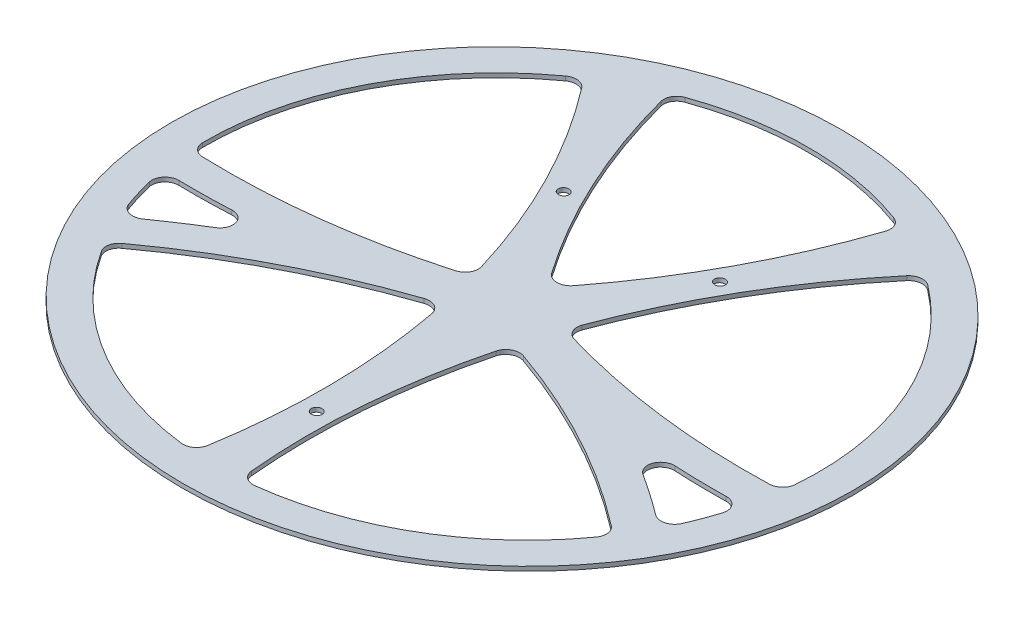
SolidWorks part; units mm, degrees
ref_plane "Front Plane" through (0, 0, 0) normal (0, 0, 1) x (1, 0, 0)
ref_plane "Top Plane" through (0, 0, 0) normal (0, 1, 0) x (1, 0, 0)
ref_plane "Right Plane" through (0, 0, 0) normal (1, 0, 0) x (0, 0, -1)
sketch3d "3DSketch1"
  line L1 (0, 87.7693, 116.125) -> (0, 80.6293, 116.125) construction
  line L2 (0, 80.6293, 116.125) -> (0, 84.5443, 116.125) construction
  line L3 (-59, 71.1385, -129.5485) -> (-59, 79.2077, -128.8425) construction
  circle A4 centre (-59, 71.1385, -129.5485) radius 2.925 construction
  circle A5 centre (-59, 79.2077, -128.8425) radius 1.425 construction
  point P20 (-59, 74.0524, -129.2935)
  point P23 (-59, 80.6273, -128.7183)
sketch "Sketch1" plane through (0, 79.1663, -2.7669) normal (0, -0.9994, 0.0349) x (0, -0.0349, -0.9994)
  line L0 (282.5006, 0) -> (-225.4994, 0) construction
  line L1 (335.28, 0) -> (-335.28, 0) construction
  line L2 (126.9846, -59) -> (125.9973, -59) construction
  line L3 (12.788, 0) -> (-12.788, 0) construction
  line L4 (126.5432, 59) -> (-119.1198, 540.9432) construction
  line L5 (126.5432, 59) -> (10.7966, 0) construction
  line L6 (-119.1198, 0) -> (125.9973, 0) construction
  circle A0 centre (28.5006, 0) radius 248.894
  circle A2 centre (-119.1198, 0) radius 4
  circle A3 centre (126.5432, -59) radius 4
  circle A4 centre (126.5432, 59) radius 4
  arc A5 (238.0819, -78.767) -> (238.0819, 78.767) centre (28.5006, 0) ccw
  circle A6 centre (126.5432, 59) radius 12.5
  circle A7 centre (126.5432, -59) radius 12.5
  circle A8 centre (-119.1198, 0) radius 12.5
  arc A9 (-184.9866, 16.621) -> (-7.7838, 24.3616) centre (-119.1198, 540.9432) ccw
  arc A10 (-184.9866, -16.621) -> (-7.7838, -24.3616) centre (-119.1198, -540.9432) cw
  arc A11 (225.9535, 84.8583) -> (66.5854, 8.1579) centre (372.2061, -422.9432) ccw
  arc A12 (225.9535, -84.8583) -> (66.5854, -8.1579) centre (372.2061, 422.9432) cw
  circle A13 centre (28.5006, 0) radius 223.894 construction
  arc A14 (205.7547, 136.7828) -> (18.3529, 223.664) centre (28.5006, 0) ccw
  arc A15 (-193.6629, -27.7839) -> (-94.7562, -186.9126) centre (28.5006, 0) ccw
  arc A16 (43.3324, 38.0899) -> (203.9515, 122.76) centre (-119.1198, 540.9432) ccw
  arc A17 (8.8118, -214.0115) -> (30.6777, -44.7397) centre (536.9543, -196.1868) cw
  arc A18 (-81.3637, -184.7117) -> (-0.4726, -37.4988) centre (-498.1628, 140.1432) ccw
  arc A19 (43.3324, -38.0899) -> (203.9515, -122.76) centre (-119.1198, -540.9432) cw
  arc A20 (-94.7562, 186.9126) -> (-193.6629, 27.7839) centre (28.5006, 0) ccw
  arc A21 (-81.3637, 184.7117) -> (-0.4726, 37.4988) centre (-498.1628, -140.1432) cw
  arc A22 (8.8118, 214.0115) -> (30.6777, 44.7397) centre (536.9543, 196.1868) ccw
  arc A23 (-52.2101, -208.8405) -> (-28.9565, -216.396) centre (28.5006, 0) ccw
  arc A24 (199.6863, -210.6797) -> (36.8105, -25.5752) centre (-267.5314, -457.58) ccw [skipped]
  arc A25 (-233.826, -69.823) -> (6.7451, -15.8063) centre (-0.9633, -544.1933) cw [skipped]
  arc A26 (-233.826, 69.823) -> (6.7451, 15.8063) centre (-0.9633, 544.1933) ccw [skipped]
  arc A27 (199.6863, 210.6797) -> (36.8105, 25.5752) centre (-267.5314, 457.58) cw [skipped]
  arc A28 (-16.392, 206.5438) -> (-15.7405, 167.4151) centre (536.9543, 196.1868) ccw
  arc A29 (-56.584, 193.4846) -> (-34.1118, 161.4459) centre (-498.1628, -140.1432) cw
  arc A30 (-28.9565, 216.396) -> (-52.2101, 208.8405) centre (28.5006, 0) ccw
  arc A31 (-10.9049, 274.6063) -> (10.4716, 25.5547) centre (536.9543, 196.1868) ccw construction
  arc A32 (-101.0292, 245.3231) -> (27.4773, 33.0673) centre (-498.1628, -140.1432) cw construction
  arc A33 (-16.392, -206.5438) -> (-15.7405, -167.4151) centre (536.9543, -196.1868) cw
  arc A34 (-56.584, -193.4846) -> (-34.1118, -161.4459) centre (-498.1628, 140.1432) ccw
  arc A35 (-10.9049, -274.6063) -> (10.4716, -25.5547) centre (536.9543, -196.1868) cw construction
  arc A36 (-101.0292, -245.3231) -> (27.4773, -33.0673) centre (-498.1628, 140.1432) ccw construction
  arc A37 (18.3529, -223.664) -> (205.7547, -136.7828) centre (28.5006, 0) ccw
  arc A38 (-56.584, 193.4846) -> (-52.2101, 208.8405) centre (-48.6052, 199.5128) cw
  arc A39 (-28.9565, 216.396) -> (-16.392, 206.5438) centre (-26.3902, 206.7309) cw
  arc A40 (-34.1118, 161.4459) -> (-15.7405, 167.4151) centre (-25.727, 166.8953) ccw
  arc A41 (-15.7405, -167.4151) -> (-34.1118, -161.4459) centre (-25.727, -166.8953) ccw
  arc A42 (-52.2101, -208.8405) -> (-56.584, -193.4846) centre (-48.6052, -199.5128) cw
  arc A43 (-28.9565, -216.396) -> (-16.392, -206.5438) centre (-26.3902, -206.7309) ccw
  arc A44 (-118.9684, -227.9109) -> (3.7332, -25.2431) centre (-498.1628, 140.1432) ccw construction
  arc A45 (-94.7562, -186.9126) -> (-81.3637, -184.7117) centre (-89.251, -178.5643) ccw
  arc A46 (-193.6629, -27.7839) -> (-184.9866, -16.621) centre (-183.7402, -26.543) cw
  arc A47 (-193.6629, 27.7839) -> (-184.9866, 16.621) centre (-183.7402, 26.543) ccw
  arc A48 (-118.9684, 227.9109) -> (3.7332, 25.2431) centre (-498.1628, -140.1432) cw construction
  arc A49 (-94.7562, 186.9126) -> (-81.3637, 184.7117) centre (-89.251, 178.5643) cw
  arc A50 (13.8428, 271.0639) -> (34.2537, 33.2625) centre (536.9543, 196.1868) ccw construction
  arc A51 (8.8118, 214.0115) -> (18.3529, 223.664) centre (18.8061, 213.6742) cw
  arc A52 (203.9515, 122.76) -> (205.7547, 136.7828) centre (197.8378, 130.6735) ccw
  arc A53 (225.9535, 84.8583) -> (238.0819, 78.767) centre (228.7211, 75.2489) cw
  arc A54 (225.9535, -84.8583) -> (238.0819, -78.767) centre (228.7211, -75.2489) ccw
  arc A55 (66.5854, -8.1579) -> (66.5854, 8.1579) centre (72.3689, 0) cw
  arc A56 (30.6777, 44.7397) -> (43.3324, 38.0899) centre (40.2583, 47.6056) ccw
  arc A57 (-7.7838, 24.3616) -> (-0.4726, 37.4988) centre (-9.8907, 34.1372) ccw
  arc A58 (-0.4726, -37.4988) -> (-7.7838, -24.3616) centre (-9.8907, -34.1372) ccw
  arc A59 (13.8428, -271.0639) -> (34.2537, -33.2625) centre (536.9543, -196.1868) cw construction
  arc A60 (43.3324, -38.0899) -> (30.6777, -44.7397) centre (40.2583, -47.6056) ccw
  arc A61 (203.9515, -122.76) -> (205.7547, -136.7828) centre (197.8378, -130.6735) cw
  arc A62 (8.8118, -214.0115) -> (18.3529, -223.664) centre (18.8061, -213.6742) ccw
  point P2 (-220.3935, 0)
  point P3 (277.3946, 0)
  point P28 (28.5006, 0)
  point P32 (0, 0)
  point P50 (0, 0)
  point P52 (55.7908, 0)
  point P66 (28.5006, 0)
  point P116 (211.6319, 128.8079)
  dimension "D1" = 8
  dimension "D3" = 25
  dimension "D9" = 10
  dimension "D10" = 10
  dimension "D2" = 25
  dimension "D5" = 25
  dimension "D6" = 25
  dimension "D7" = 25
  dimension "D8" = 25
  dimension "D4" = 5
extrude "Boss-Extrude1" add sketch "Sketch1" along normal mid plane 3.175 contours A0 A62 A17 A60 A19 A7 A12 A55 A11 A6 A16 A56 A22 A51 A14 A52 A53 A5 A54 A61 A37 A58 A18 A45 A15 A46 A10 A8 A9 A47 A20 A49 A21 A57 A43 A23 A42 A34 A41 | A7 A3 | A6 A4 | A8 A2
